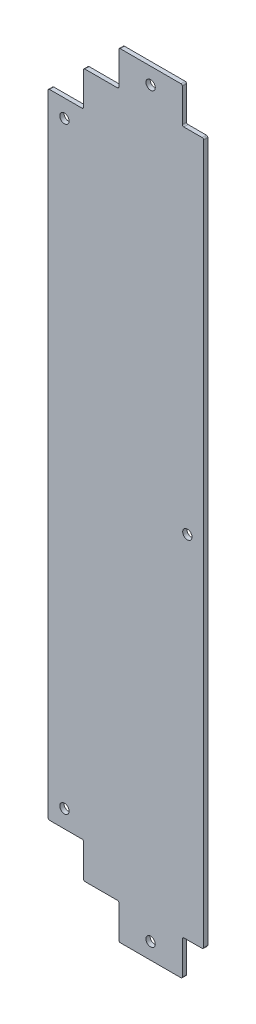
SolidWorks part; units mm, degrees
material "Acrylic (Medium-high impact)"
ref_plane "Front Plane" through (0, 0, 0) normal (0, 0, 1) x (1, 0, 0)
ref_plane "Top Plane" through (0, 0, 0) normal (0, 1, 0) x (1, 0, 0)
ref_plane "Right Plane" through (0, 0, 0) normal (1, 0, 0) x (0, 0, -1)
sketch "Sketch1" plane through (0, 0, 0) normal (0, 0, 1) x (1, 0, 0)
  line L0 (26, 473) -> (49, 473)
  line L1 (51, -50) -> (94, -50)
  line L2 (0, 1) -> (0, 447)
  line L3 (51, 498) -> (94, 498)
  line L4 (110, -23.5) -> (110, 471.5)
  line L7 (109, -24.5) -> (96, -24.5)
  line L8 (95, -49) -> (95, -25.5)
  line L11 (1, 0) -> (24, 0)
  line L12 (25, -24) -> (25, -1)
  line L15 (1, 448) -> (24, 448)
  line L16 (25, 472) -> (25, 449)
  line L19 (109, 472.5) -> (96, 472.5)
  line L20 (95, 497) -> (95, 473.5)
  line L21 (50, 474) -> (50, 497)
  line L22 (26, -25) -> (49, -25)
  line L23 (50, -26) -> (50, -49)
  arc A0 (0, 1) -> (1, 0) centre (1, 1) ccw
  arc A1 (24, 0) -> (25, -1) centre (24, -1) cw
  arc A2 (26, -25) -> (25, -24) centre (26, -24) cw
  arc A3 (49, -25) -> (50, -26) centre (49, -26) cw
  arc A4 (50, -49) -> (51, -50) centre (51, -49) ccw
  arc A5 (94, -50) -> (95, -49) centre (94, -49) ccw
  arc A6 (96, -24.5) -> (95, -25.5) centre (96, -25.5) ccw
  arc A7 (110, -23.5) -> (109, -24.5) centre (109, -23.5) cw
  arc A8 (110, 471.5) -> (109, 472.5) centre (109, 471.5) ccw
  arc A9 (96, 472.5) -> (95, 473.5) centre (96, 473.5) cw
  arc A10 (94, 498) -> (95, 497) centre (94, 497) cw
  arc A11 (50, 497) -> (51, 498) centre (51, 497) cw
  arc A12 (49, 473) -> (50, 474) centre (49, 474) ccw
  arc A13 (26, 473) -> (25, 472) centre (26, 472) ccw
  arc A14 (24, 448) -> (25, 449) centre (24, 449) ccw
  arc A15 (0, 447) -> (1, 448) centre (1, 447) cw
  point P0 (12.5, 448)
  point P19 (0, 0)
  point P25 (25, -25)
  point P28 (50, -25)
  point P31 (50, -50)
  point P34 (95, -50)
  point P37 (95, -24.5)
  point P44 (95, 472.5)
  point P47 (95, 498)
  point P50 (50, 498)
  point P53 (50, 473)
  point P56 (25, 473)
  dimension "D14" = 1
  dimension "D1" = 110
  dimension "D2" = 548
  dimension "D3" = 25.5
  dimension "D4" = 15
  dimension "D5" = 50
  dimension "D6" = 25
  dimension "D7" = 25.5
  dimension "D8" = 25
  dimension "D9" = 50
  dimension "D10" = 25
  dimension "D11" = 25
  dimension "D12" = 50
  dimension "D13" = 50
extrude "Boss-Extrude1" add sketch "Sketch1" along normal blind 3
hole_wizard "M6 Clearance Hole1" positions "Sketch2" profile "Sketch3" hole size "M6" standard "ANSI Metric" end condition up to next
sketch "Sketch2" plane through (0, 0, 0) normal (0, 0, -1) x (-1, 0, 0)
  line L0 (-51, -50) -> (-94, -50) construction
  line L1 (-94, 498) -> (-51, 498) construction
  line L2 (0, 447) -> (0, 1) construction
  line L3 (-1, 0) -> (-24, 0) construction
  line L4 (-24, 448) -> (-1, 448) construction
  point P0 (-72.5, -38.5)
  point P2 (-11.5, 12.5)
  point P4 (-11.5, 435.5)
  point P6 (-72.5, 486.5)
  point P12 (-72.5, -50)
  dimension "D1" = 11.5
  dimension "D2" = 11.5
  dimension "D3" = 11.5
  dimension "D4" = 12.5
  dimension "D5" = 12.5
sketch "Sketch3" plane through (72.5, -38.5, 0) normal (1, 0, 0) x (0, 1, 0)
  line L0 (0, 0) -> (0, 3)
  line L1 (0, 3) -> (3.3, 3)
  line L2 (3.3, 3) -> (3.3, 0)
  line L5 (3.3, 0) -> (0, 0)
  line L11 (0, -6.35) -> (0, 107.95) construction
  dimension "Thru Hole Dia." = 6.6
  dimension "Thru Hole Depth" = 3
hole_wizard "M6 Clearance Hole2" positions "Sketch4" profile "Sketch5" hole size "M6" standard "ANSI Metric" end condition up to next
sketch "Sketch4" plane through (0, 0, 0) normal (0, 0, -1) x (-1, 0, 0)
  point P0 (-98.5, 224)
sketch "Sketch5" plane through (98.5, 224, 0) normal (1, 0, 0) x (0, 1, 0)
  line L0 (0, 0) -> (0, 3)
  line L1 (0, 3) -> (3.3, 3)
  line L2 (3.3, 3) -> (3.3, 0)
  line L5 (3.3, 0) -> (0, 0)
  line L11 (0, -6.35) -> (0, 107.95) construction
  dimension "Thru Hole Dia." = 6.6
  dimension "Thru Hole Depth" = 3
